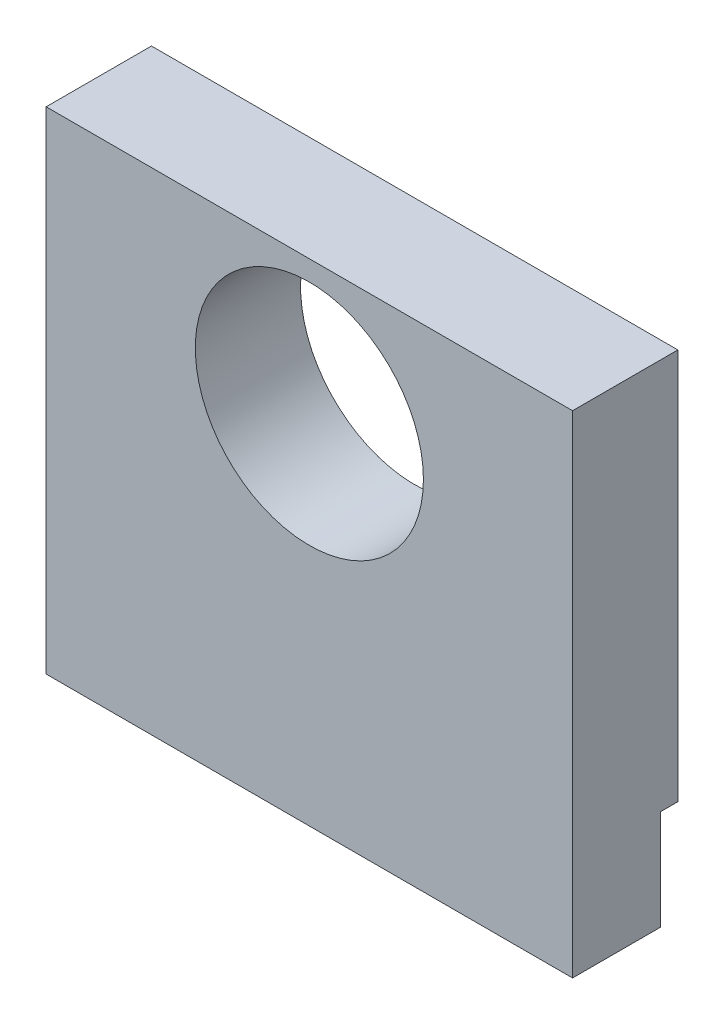
SolidWorks part; units mm, degrees
ref_plane "Спереди" through (0, 0, 0) normal (0, 0, 1) x (1, 0, 0)
ref_plane "Сверху" through (0, 0, 0) normal (0, 1, 0) x (1, 0, 0)
ref_plane "Справа" through (0, 0, 0) normal (1, 0, 0) x (0, 0, -1)
sketch "Эскиз1" plane through (-15, 0, 0) normal (-1, 0, 0) x (0, 0, 1)
  line L0 (137, 2.7) -> (137, 10.6) construction
  line L1 (138, 2.7) -> (138, -3) construction
  line L2 (137, 2.7) -> (138, 2.7) construction
  line L3 (137, 2.7) -> (137, 25)
  line L4 (138, 2.7) -> (138, -3)
  line L5 (137, 2.7) -> (138, 2.7)
  line L6 (137, 25) -> (143, 25)
  line L7 (143, -3) -> (138, -3)
  line L8 (143, 25) -> (143, -3)
  dimension "D1" = 6
  dimension "D2" = 28
extrude "Body" add sketch "Эскиз1" against normal up to surface (30 mm away) contours L6 L8 L7 L4 L5 L3
sketch "Эскиз4" plane through (0, 0, 143) normal (0, 0, 1) x (1, 0, 0)
  line L0 (0, 4.75) -> (0, 25) construction
  line L4 (15, 25) -> (-15, 25) construction
  circle A0 centre (0, 17.35) radius 6.5
  dimension "D1" = 13
  dimension "D2" = 7.65
extrude "Bearing_Hole" cut sketch "Эскиз4" against normal up to surface (6 mm away) up to face at (0, 13.85, 137)
